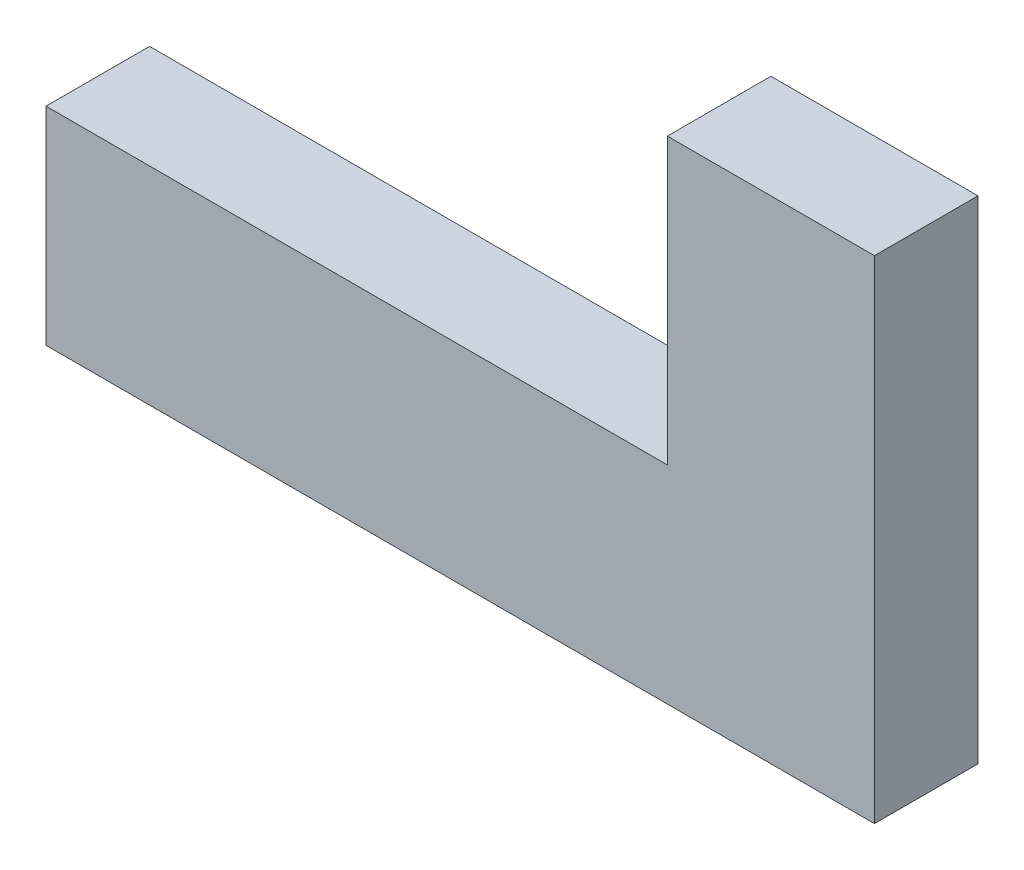
SolidWorks part; units mm, degrees
ref_plane "Front Plane" through (0, 0, 0) normal (0, 0, 1) x (1, 0, 0)
ref_plane "Top Plane" through (0, 0, 0) normal (0, 1, 0) x (1, 0, 0)
ref_plane "Right Plane" through (0, 0, 0) normal (1, 0, 0) x (0, 0, -1)
sketch "Sketch1" plane through (0, 0, 0) normal (0, 0, 1) x (1, 0, 0)
  line L0 (0, 10.16) -> (30.48, 10.16)
  line L1 (0, 0) -> (40.64, 0)
  line L2 (0, 0) -> (0, 10.16)
  line L3 (0, 10.16) -> (40.64, 10.16) construction
  line L4 (40.64, 0) -> (40.64, 10.16)
  line L5 (40.64, 10.16) -> (30.48, 10.16) construction
  line L6 (40.64, 10.16) -> (40.64, 24.13)
  line L7 (40.64, 24.13) -> (30.48, 24.13)
  line L8 (30.48, 10.16) -> (30.48, 24.13)
  dimension "D1" = 40.64
  dimension "D2" = 10.16
  dimension "D3" = 13.97
  dimension "D4" = 10.16
extrude "Boss-Extrude1" add sketch "Sketch1" along normal blind 5.08
